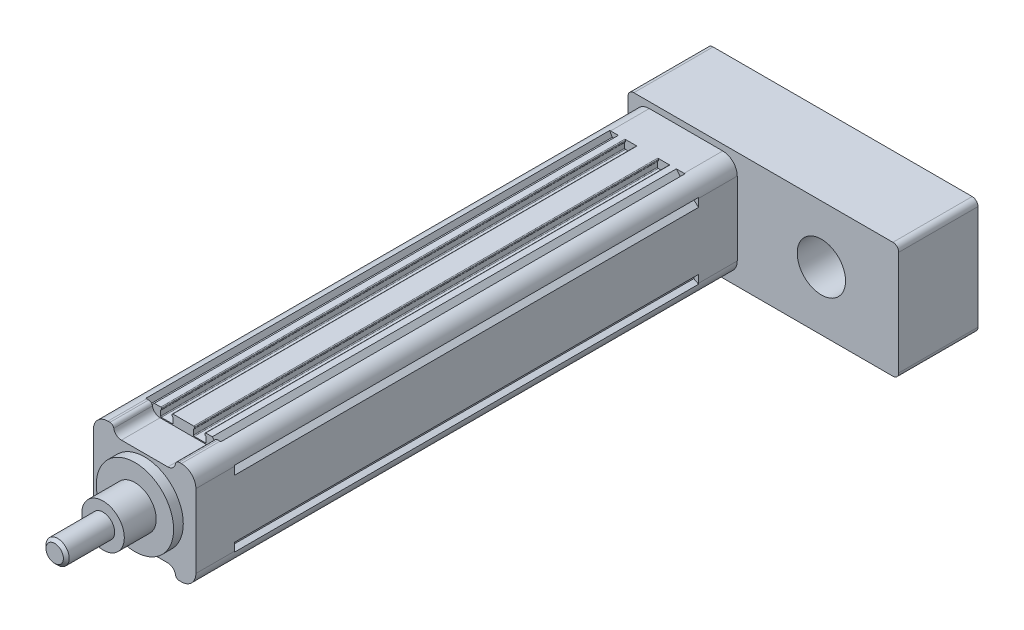
SolidWorks part; units mm, degrees
ref_plane "Front" through (0, 0, 0) normal (0, 0, 1) x (1, 0, 0)
ref_plane "Top" through (0, 0, 0) normal (0, 1, 0) x (1, 0, 0)
ref_plane "Right" through (0, 0, 0) normal (1, 0, 0) x (0, 0, -1)
sketch "草图1" plane through (0, 0, 0) normal (0, 0, 1) x (1, 0, 0)
  line L0 (19.7737, 3) -> (23.3, 3)
  line L1 (23.3, 3) -> (23.3, -3)
  line L2 (23.3, -3) -> (19.7737, -3)
  line L3 (-19.7737, -3) -> (-23.3, -3)
  line L4 (-23.3, -3) -> (-23.3, 3)
  line L5 (-23.3, 3) -> (-19.7737, 3)
  line L6 (-18.2, 24) -> (-19.4434, 26.4869)
  line L7 (-26.4869, 19.4434) -> (-24, 18.2)
  line L8 (-24, 18.2) -> (-24, 17.1)
  line L9 (-24, 17.1) -> (-26.5, 15)
  line L10 (-26.5, 15) -> (-26.5, -15)
  line L11 (-26.5, -15) -> (-24, -17.1)
  line L12 (-24, -17.1) -> (-24, -18.2)
  line L13 (-24, -18.2) -> (-26.4869, -19.4434)
  line L14 (-19.4434, -26.4869) -> (-18.2, -24)
  line L15 (-18.2, -24) -> (-17.1, -24)
  line L16 (-17.1, -24) -> (-15, -26.5)
  line L17 (-15, -26.5) -> (-11.65, -26.5)
  line L18 (-11.25, -26.1) -> (-11.25, -25.6)
  line L19 (-11.65, -25.2) -> (-11.75, -25.2)
  line L20 (-11.75, -25.2) -> (-11.75, -22.4)
  line L21 (-11.35, -22) -> (-5.65, -22)
  line L22 (-5.25, -22.4) -> (-5.25, -25.2)
  line L23 (-5.25, -25.2) -> (-5.35, -25.2)
  line L24 (-5.75, -25.6) -> (-5.75, -26.1)
  line L25 (-5.35, -26.5) -> (5.35, -26.5)
  line L26 (5.75, -26.1) -> (5.75, -25.6)
  line L27 (5.35, -25.2) -> (5.25, -25.2)
  line L28 (5.25, -25.2) -> (5.25, -22.4)
  line L29 (5.65, -22) -> (11.35, -22)
  line L30 (11.75, -22.4) -> (11.75, -25.2)
  line L31 (11.75, -25.2) -> (11.65, -25.2)
  line L32 (11.25, -25.6) -> (11.25, -26.1)
  line L33 (11.65, -26.5) -> (15, -26.5)
  line L34 (15, -26.5) -> (17.1, -24)
  line L35 (17.1, -24) -> (18.2, -24)
  line L36 (18.2, -24) -> (19.4434, -26.4869)
  line L37 (26.4869, -19.4434) -> (24, -18.2)
  line L38 (24, -18.2) -> (24, -17.1)
  line L39 (24, -17.1) -> (26.5, -15)
  line L40 (26.5, -15) -> (26.5, 15)
  line L41 (26.5, 15) -> (24, 17.1)
  line L42 (24, 17.1) -> (24, 18.2)
  line L43 (24, 18.2) -> (26.4869, 19.4434)
  line L44 (19.4434, 26.4869) -> (18.2, 24)
  line L45 (18.2, 24) -> (17.1, 24)
  line L46 (17.1, 24) -> (15, 26.5)
  line L47 (15, 26.5) -> (11.65, 26.5)
  line L48 (11.25, 26.1) -> (11.25, 25.6)
  line L49 (11.65, 25.2) -> (11.75, 25.2)
  line L50 (11.75, 25.2) -> (11.75, 22.4)
  line L51 (11.35, 22) -> (5.65, 22)
  line L52 (5.25, 22.4) -> (5.25, 25.2)
  line L53 (5.25, 25.2) -> (5.35, 25.2)
  line L54 (5.75, 25.6) -> (5.75, 26.1)
  line L55 (5.35, 26.5) -> (-5.35, 26.5)
  line L56 (-5.75, 26.1) -> (-5.75, 25.6)
  line L57 (-5.35, 25.2) -> (-5.25, 25.2)
  line L58 (-5.25, 25.2) -> (-5.25, 22.4)
  line L59 (-5.65, 22) -> (-11.35, 22)
  line L60 (-11.75, 22.4) -> (-11.75, 25.2)
  line L61 (-11.75, 25.2) -> (-11.65, 25.2)
  line L62 (-11.25, 25.6) -> (-11.25, 26.1)
  line L63 (-11.65, 26.5) -> (-15, 26.5)
  line L64 (-15, 26.5) -> (-17.1, 24)
  line L65 (-17.1, 24) -> (-18.2, 24)
  arc A0 (19.7737, 3) -> (-19.7737, 3) centre (0, 0) ccw
  arc A1 (-19.7737, -3) -> (19.7737, -3) centre (0, 0) ccw
  circle A2 centre (19, 19) radius 2.1
  circle A3 centre (19, -19) radius 2.1
  circle A4 centre (-19, -19) radius 2.1
  circle A5 centre (-19, 19) radius 2.1
  arc A6 (-19.4434, 26.4869) -> (-26.4869, 19.4434) centre (-19, 19) ccw
  arc A7 (-26.4869, -19.4434) -> (-19.4434, -26.4869) centre (-19, -19) ccw
  arc A8 (-11.65, -26.5) -> (-11.25, -26.1) centre (-11.65, -26.1) ccw
  arc A9 (-11.25, -25.6) -> (-11.65, -25.2) centre (-11.65, -25.6) ccw
  arc A10 (-11.35, -22) -> (-11.75, -22.4) centre (-11.35, -22.4) ccw
  arc A11 (-5.25, -22.4) -> (-5.65, -22) centre (-5.65, -22.4) ccw
  arc A12 (-5.35, -25.2) -> (-5.75, -25.6) centre (-5.35, -25.6) ccw
  arc A13 (-5.75, -26.1) -> (-5.35, -26.5) centre (-5.35, -26.1) ccw
  arc A14 (5.35, -26.5) -> (5.75, -26.1) centre (5.35, -26.1) ccw
  arc A15 (5.75, -25.6) -> (5.35, -25.2) centre (5.35, -25.6) ccw
  arc A16 (5.65, -22) -> (5.25, -22.4) centre (5.65, -22.4) ccw
  arc A17 (11.75, -22.4) -> (11.35, -22) centre (11.35, -22.4) ccw
  arc A18 (11.65, -25.2) -> (11.25, -25.6) centre (11.65, -25.6) ccw
  arc A19 (11.25, -26.1) -> (11.65, -26.5) centre (11.65, -26.1) ccw
  arc A20 (19.4434, -26.4869) -> (26.4869, -19.4434) centre (19, -19) ccw
  arc A21 (26.4869, 19.4434) -> (19.4434, 26.4869) centre (19, 19) ccw
  arc A22 (11.65, 26.5) -> (11.25, 26.1) centre (11.65, 26.1) ccw
  arc A23 (11.25, 25.6) -> (11.65, 25.2) centre (11.65, 25.6) ccw
  arc A24 (11.35, 22) -> (11.75, 22.4) centre (11.35, 22.4) ccw
  arc A25 (5.25, 22.4) -> (5.65, 22) centre (5.65, 22.4) ccw
  arc A26 (5.35, 25.2) -> (5.75, 25.6) centre (5.35, 25.6) ccw
  arc A27 (5.75, 26.1) -> (5.35, 26.5) centre (5.35, 26.1) ccw
  arc A28 (-5.35, 26.5) -> (-5.75, 26.1) centre (-5.35, 26.1) ccw
  arc A29 (-5.75, 25.6) -> (-5.35, 25.2) centre (-5.35, 25.6) ccw
  arc A30 (-5.65, 22) -> (-5.25, 22.4) centre (-5.65, 22.4) ccw
  arc A31 (-11.75, 22.4) -> (-11.35, 22) centre (-11.35, 22.4) ccw
  arc A32 (-11.65, 25.2) -> (-11.25, 25.6) centre (-11.65, 25.6) ccw
  arc A33 (-11.25, 26.1) -> (-11.65, 26.5) centre (-11.65, 26.1) ccw
extrude "凸台-拉伸1" add sketch "草图1" along normal blind 240
sketch "草图6" plane through (0, 0, 240) normal (0, 0, 1) x (1, 0, 0)
  line L0 (0, 0) -> (19, 0) construction
  line L2 (-26.5, -19) -> (-26.5, 19)
  line L3 (-19, 26.5) -> (-17.9161, 26.5)
  line L4 (26.5, -19) -> (26.5, 19)
  line L5 (-26.5, -26.5) -> (26.5, 26.5) construction
  line L6 (-26.5, 26.5) -> (26.5, -26.5) construction
  line L7 (-12, 21.5) -> (12, 21.5)
  line L9 (19, 26.5) -> (17.9161, 26.5)
  line L10 (19, -26.5) -> (17.9161, -26.5)
  line L11 (-12, -21.5) -> (12, -21.5)
  line L12 (-19, -26.5) -> (-17.9161, -26.5)
  arc A0 (12, 21.5) -> (15.9441, 24.8333) centre (12, 25.5) ccw
  arc A1 (-15.9441, 24.8333) -> (-12, 21.5) centre (-12, 25.5) ccw
  arc A2 (-15.9441, 24.8333) -> (-17.9161, 26.5) centre (-17.9161, 24.5) ccw
  arc A3 (15.9441, 24.8333) -> (17.9161, 26.5) centre (17.9161, 24.5) cw
  arc A4 (-26.5, -19) -> (-19, -26.5) centre (-19, -19) ccw
  arc A5 (19, -26.5) -> (26.5, -19) centre (19, -19) ccw
  arc A6 (26.5, 19) -> (19, 26.5) centre (19, 19) ccw
  arc A7 (-26.5, 19) -> (-19, 26.5) centre (-19, 19) cw
  arc A8 (15.9441, -24.8333) -> (17.9161, -26.5) centre (17.9161, -24.5) ccw
  arc A9 (12, -21.5) -> (15.9441, -24.8333) centre (12, -25.5) cw
  arc A10 (-15.9441, -24.8333) -> (-12, -21.5) centre (-12, -25.5) cw
  arc A11 (-15.9441, -24.8333) -> (-17.9161, -26.5) centre (-17.9161, -24.5) cw
  point P0 (0, 0)
  point P9 (0, 21.5)
  point P13 (20, 20.8461)
  point P16 (-12, 20.8461)
  dimension "D5" = 4
  dimension "D6" = 2
  dimension "D7" = 2
  dimension "D9" = 7.5
  dimension "D1" = 53
  dimension "D2" = 53
  dimension "D3" = 26.5
  dimension "D4" = 24
  dimension "D8" = 5
extrude "凸台-拉伸2" add sketch "草图6" along normal blind 20
sketch "草图7" plane through (0, 0, 260) normal (0, 0, 1) x (1, 0, 0)
  circle A0 centre (0, 0) radius 20
  dimension "D1" = 40
extrude "凸台-拉伸3" add sketch "草图7" along normal blind 5
sketch "草图9" plane through (0, 0, 265) normal (0, 0, 1) x (1, 0, 0)
  circle A0 centre (0, 0) radius 11
  dimension "D1" = 22
extrude "凸台-拉伸4" add sketch "草图9" along normal blind 16.5
sketch "草图10" plane through (0, 0, 281.5) normal (0, 0, 1) x (1, 0, 0)
  circle A0 centre (0, 0) radius 6
  dimension "D1" = 12
extrude "凸台-拉伸5" add sketch "草图10" along normal blind 25
sketch "草图11" plane through (0, 0, 0) normal (0, 0, -1) x (-1, 0, 0)
  line L1 (-19, -26.5) -> (19, -26.5)
  line L2 (-26.5, -19) -> (-26.5, 19)
  line L3 (-19, 26.5) -> (19, 26.5)
  line L4 (26.5, -19) -> (26.5, 19)
  line L5 (-26.5, -26.5) -> (26.5, 26.5) construction
  line L6 (-26.5, 26.5) -> (26.5, -26.5) construction
  arc A0 (-26.5, -19) -> (-19, -26.5) centre (-19, -19) ccw
  arc A1 (19, -26.5) -> (26.5, -19) centre (19, -19) ccw
  arc A2 (26.5, 19) -> (19, 26.5) centre (19, 19) ccw
  arc A3 (-26.5, 19) -> (-19, 26.5) centre (-19, 19) cw
  point P0 (0, 0)
  dimension "D3" = 7.5
  dimension "D1" = 53
  dimension "D2" = 53
extrude "凸台-拉伸6" add sketch "草图11" along normal blind 20
sketch "草图12" plane through (0, 0, -20) normal (0, 0, -1) x (-1, 0, 0)
  line L1 (-107, -30.4042) -> (27, -30.4042)
  line L2 (-110, -27.4042) -> (-110, 26.5958)
  line L3 (-107, 29.5958) -> (27, 29.5958)
  line L4 (30, -27.4042) -> (30, 26.5958)
  line L5 (-110, -30.4042) -> (30, 29.5958) construction
  line L6 (-110, 29.5958) -> (30, -30.4042) construction
  arc A0 (27, 29.5958) -> (30, 26.5958) centre (27, 26.5958) cw
  arc A1 (30, -27.4042) -> (27, -30.4042) centre (27, -27.4042) cw
  arc A2 (-110, -27.4042) -> (-107, -30.4042) centre (-107, -27.4042) ccw
  arc A3 (-110, 26.5958) -> (-107, 29.5958) centre (-107, 26.5958) cw
  point P0 (-40, -0.4042)
  dimension "D4" = 3
  dimension "D1" = 60
  dimension "D2" = 140
  dimension "D3" = 30
extrude "凸台-拉伸7" add sketch "草图12" along normal blind 41
sketch "草图13" plane through (0, 0, -20) normal (0, 0, 1) x (1, 0, 0)
  circle A0 centre (70, 0) radius 12.5
  dimension "D2" = 25
  dimension "D1" = 70
extrude "切除-拉伸2" cut sketch "草图13" against normal blind 30
hole_wizard "M6 螺纹孔1" positions "草图14" profile "草图15" tap size "M6" standard "GB"
sketch "草图14" plane through (0, 0, -61) normal (0, 0, -1) x (-1, 0, 0)
  line L0 (30, -27.4042) -> (30, 26.5958) construction
  point P0 (19, -19)
  dimension "D1" = 11
  dimension "D2" = 19
sketch "草图15" plane through (-19, -19, -61) normal (1, 0, 0) x (0, 1, 0)
  line L0 (0, 0) -> (0, 16.5022)
  line L1 (0, 16.5022) -> (2.5, 15)
  line L2 (2.5, 15) -> (2.5, 0)
  line L5 (2.5, 0) -> (0, 0)
  line L10 (0, 16.5022) -> (-2.5, 15) construction
  line L11 (0, -6.35) -> (0, 107.95) construction
  dimension "螺纹孔钻头直径" = 5
  dimension "螺纹孔钻头深度" = 15
  dimension "导头角度" = 118
cosmetic thread "孔螺蚊线4" parameters "D1"=12, "D2"=6
pattern_linear "阵列(线性)1" count 2 spacing 38 along (0, 1, 0) count 2 spacing 38 along (1, 0, 0) of "M6 螺纹孔1"
hole_wizard "M6 螺纹孔2" positions "草图16" profile "草图17" tap size "M6" standard "GB"
sketch "草图16" plane through (0, 0, -61) normal (0, 0, -1) x (-1, 0, 0)
  circle A1 centre (-19, 19) radius 2.5 construction
  circle A2 centre (-19, -19) radius 2.5 construction
  point P0 (-84, -19)
  point P2 (-84, 19)
  dimension "D3" = 65
  dimension "D1" = 19
  dimension "D2" = 19
  dimension "D4" = 65
sketch "草图17" plane through (84, -19, -61) normal (1, 0, 0) x (0, 1, 0)
  line L0 (0, 0) -> (0, 16.5022)
  line L1 (0, 16.5022) -> (2.5, 15)
  line L2 (2.5, 15) -> (2.5, 0)
  line L5 (2.5, 0) -> (0, 0)
  line L10 (0, 16.5022) -> (-2.5, 15) construction
  line L11 (0, -6.35) -> (0, 107.95) construction
  dimension "螺纹孔钻头直径" = 5
  dimension "螺纹孔钻头深度" = 15
  dimension "导头角度" = 118
cosmetic thread "孔螺蚊线5" parameters "D1"=12, "D2"=6
cosmetic thread "孔螺蚊线6" parameters "D1"=12, "D2"=6
hole_wizard "M6 螺纹孔3" positions "草图19" profile "草图20" tap size "M6" standard "GB"
sketch "草图19" plane through (-26.5, 0, 0) normal (-1, 0, 0) x (0, 0, 1)
  line L0 (260, 19) -> (260, -19) construction
  point P0 (250, 11)
  point P2 (250, -11)
  dimension "D1" = 10
  dimension "D2" = 10
  dimension "D3" = 22
  dimension "D4" = 11
sketch "草图20" plane through (-26.5, 11, 250) normal (0, 1, 0) x (0, 0, 1)
  line L0 (0, 0) -> (0, 16.5022)
  line L1 (0, 16.5022) -> (2.5, 15)
  line L2 (2.5, 15) -> (2.5, 0)
  line L5 (2.5, 0) -> (0, 0)
  line L10 (0, 16.5022) -> (-2.5, 15) construction
  line L11 (0, -6.35) -> (0, 107.95) construction
  dimension "螺纹孔钻头直径" = 5
  dimension "螺纹孔钻头深度" = 15
  dimension "导头角度" = 118
cosmetic thread "孔螺蚊线7" parameters "D1"=12, "D2"=6
cosmetic thread "孔螺蚊线8" parameters "D1"=12, "D2"=6
hole_wizard "M6 螺纹孔4" positions "草图21" profile "草图22" tap size "M6" standard "GB"
sketch "草图21" plane through (-26.5, 0, 0) normal (-1, 0, 0) x (0, 0, 1)
  line L0 (-20, -27.4042) -> (-20, 26.5958) construction
  line L1 (-20, -19) -> (-20, 19) construction
  point P0 (-10, 11)
  point P2 (-10, -11)
  dimension "D1" = 10
  dimension "D2" = 10
  dimension "D3" = 11
  dimension "D4" = 11
sketch "草图22" plane through (-26.5, 11, -10) normal (0, 1, 0) x (0, 0, 1)
  line L0 (0, 0) -> (0, 16.5022)
  line L1 (0, 16.5022) -> (2.5, 15)
  line L2 (2.5, 15) -> (2.5, 0)
  line L5 (2.5, 0) -> (0, 0)
  line L10 (0, 16.5022) -> (-2.5, 15) construction
  line L11 (0, -6.35) -> (0, 107.95) construction
  dimension "螺纹孔钻头直径" = 5
  dimension "螺纹孔钻头深度" = 15
  dimension "导头角度" = 118
cosmetic thread "孔螺蚊线9" parameters "D1"=12, "D2"=6
cosmetic thread "孔螺蚊线10" parameters "D1"=12, "D2"=6
chamfer "倒角1" distance 1.5 angle 45 1 edges at (6, 0, 306.5)
sketch "草图23" plane through (0, 0, 281.5) normal (0, 0, 1) x (1, 0, 0)
  line L1 (10.9697, 0) -> (5.4848, 9.5)
  line L2 (5.4848, 9.5) -> (-5.4848, 9.5)
  line L3 (-5.4848, 9.5) -> (-10.9697, 0)
  line L4 (-10.9697, 0) -> (-5.4848, -9.5)
  line L5 (-5.4848, -9.5) -> (5.4848, -9.5)
  line L6 (5.4848, -9.5) -> (10.9697, 0)
  circle A0 centre (0, 0) radius 9.5 construction
  dimension "D1" = 19
